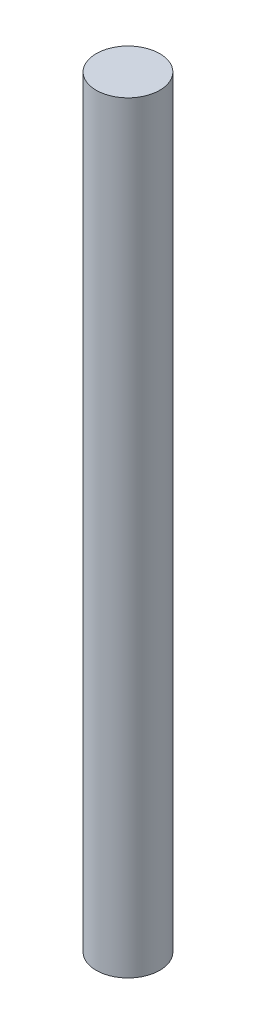
SolidWorks part; units mm, degrees
ref_plane "前视基准面" through (0, 0, 0) normal (0, 0, 1) x (1, 0, 0)
ref_plane "上视基准面" through (0, 0, 0) normal (0, 1, 0) x (1, 0, 0)
ref_plane "右视基准面" through (0, 0, 0) normal (1, 0, 0) x (0, 0, -1)
sketch "草图1" plane through (0, 0, 0) normal (0, 1, 0) x (1, 0, 0)
  circle A0 centre (0, 0) radius 1.5
extrude "凸台-拉伸1" add sketch "草图1" along normal blind 36
